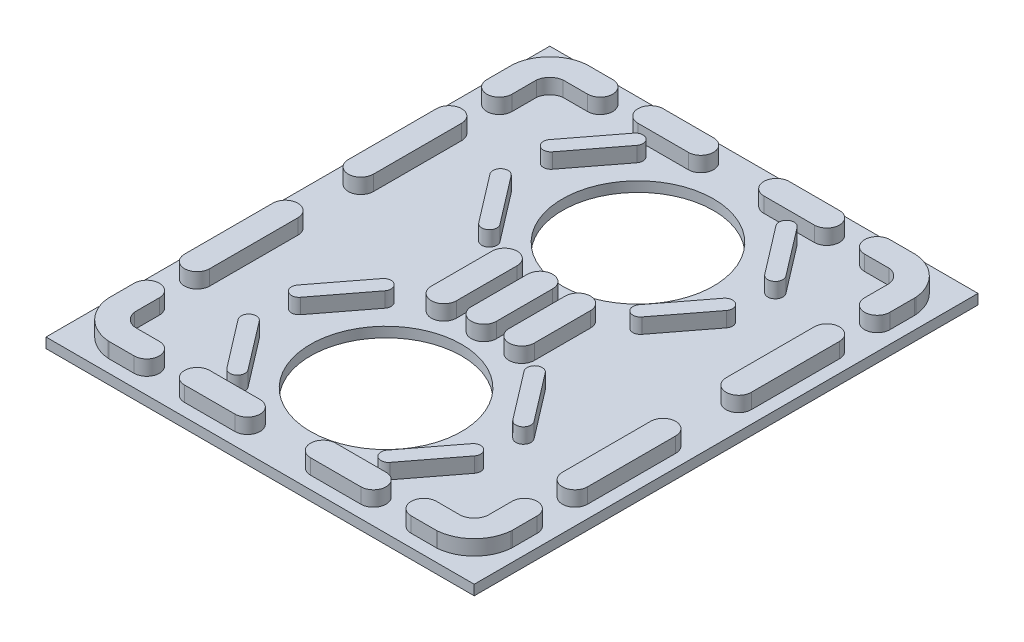
SolidWorks part; units mm, degrees
ref_plane "Front Plane" through (0, 0, 0) normal (0, 0, 1) x (1, 0, 0)
ref_plane "Top Plane" through (0, 0, 0) normal (0, 1, 0) x (1, 0, 0)
ref_plane "Right Plane" through (0, 0, 0) normal (1, 0, 0) x (0, 0, -1)
sketch "Sketch1" plane through (0, 0, 0) normal (0, 1, 0) x (1, 0, 0)
  line L1 (0, 0) -> (170, 0)
  line L2 (0, 0) -> (0, 200)
  line L3 (0, 200) -> (170, 200)
  line L4 (170, 0) -> (170, 200)
  dimension "D1" = 200
  dimension "D2" = 170
extrude "Boss-Extrude1" add sketch "Sketch1" along normal blind 4
sketch "Sketch3" plane through (0, 4, 0) normal (0, 1, 0) x (1, 0, 0)
  line L0 (0, 0) -> (20, 0)
  line L1 (0, 0) -> (170, 0) construction
  line L2 (20, 0) -> (20, 10)
  line L3 (0, 0) -> (0, 20)
  line L4 (0, 200) -> (0, 0) construction
  line L5 (0, 20) -> (10, 20)
  line L6 (10, 20) -> (10, 30) construction
  line L7 (5, 20) -> (5, 30)
  line L8 (15, 20) -> (15, 30)
  line L9 (20, 10) -> (30, 10) construction
  line L10 (20, 15) -> (30, 15)
  line L11 (20, 5) -> (30, 5)
  line L12 (0, 100) -> (170, 100) construction
  line L13 (170, 0) -> (170, 200) construction
  line L14 (85, 0) -> (85, 200) construction
  line L15 (170, 200) -> (0, 200) construction
  line L16 (10, 50) -> (10, 85) construction
  line L17 (5, 50) -> (5, 85)
  line L18 (15, 50) -> (15, 85)
  line L19 (50, 10) -> (70, 10) construction
  line L20 (50, 15) -> (70, 15)
  line L21 (50, 5) -> (70, 5)
  line L22 (160, 50) -> (160, 85) construction
  line L23 (165, 50) -> (165, 85)
  line L24 (155, 50) -> (155, 85)
  line L25 (160, 20) -> (160, 30) construction
  line L26 (165, 20) -> (165, 30)
  line L27 (155, 20) -> (155, 30)
  line L28 (150, 10) -> (140, 10) construction
  line L29 (150, 15) -> (140, 15)
  line L30 (150, 5) -> (140, 5)
  line L31 (120, 10) -> (100, 10) construction
  line L32 (120, 15) -> (100, 15)
  line L33 (120, 5) -> (100, 5)
  line L34 (160, 150) -> (160, 115) construction
  line L35 (165, 150) -> (165, 115)
  line L36 (155, 150) -> (155, 115)
  line L37 (160, 180) -> (160, 170) construction
  line L38 (165, 180) -> (165, 170)
  line L39 (155, 180) -> (155, 170)
  line L40 (150, 190) -> (140, 190) construction
  line L41 (150, 185) -> (140, 185)
  line L42 (150, 195) -> (140, 195)
  line L43 (120, 190) -> (100, 190) construction
  line L44 (120, 185) -> (100, 185)
  line L45 (120, 195) -> (100, 195)
  line L46 (50, 190) -> (70, 190) construction
  line L47 (50, 185) -> (70, 185)
  line L48 (50, 195) -> (70, 195)
  line L49 (20, 190) -> (30, 190) construction
  line L50 (20, 185) -> (30, 185)
  line L51 (20, 195) -> (30, 195)
  line L52 (10, 180) -> (10, 170) construction
  line L53 (5, 180) -> (5, 170)
  line L54 (15, 180) -> (15, 170)
  line L55 (10, 150) -> (10, 115) construction
  line L56 (5, 150) -> (5, 115)
  line L57 (15, 150) -> (15, 115)
  line L58 (170, 100) -> (170, 50) construction
  line L59 (170, 50) -> (0, 50) construction
  line L60 (170, 100) -> (170, 150) construction
  line L61 (170, 150) -> (0, 150) construction
  line L62 (85, 111.1607) -> (85, 88.8393) construction
  line L63 (90, 111.1607) -> (90, 88.8393)
  line L64 (80, 111.1607) -> (80, 88.8393)
  line L65 (100, 111.157) -> (100, 88.843) construction
  line L68 (70, 112.0369) -> (70, 87.9631) construction
  line L69 (75, 112.0369) -> (75, 87.9631)
  line L70 (65, 112.0369) -> (65, 87.9631)
  line L71 (105, 111.157) -> (105, 88.843)
  line L72 (95, 111.157) -> (95, 88.843)
  line L73 (40.4617, 40) -> (55, 21.0063) construction
  line L74 (42.844, 41.8234) -> (57.3822, 22.8297)
  line L75 (38.0795, 38.1766) -> (52.6178, 19.1828)
  line L76 (129.5383, 40) -> (115, 21.0063) construction
  line L77 (127.156, 41.8234) -> (112.6178, 22.8297)
  line L78 (131.9205, 38.1766) -> (117.3822, 19.1828)
  line L79 (129.5383, 60) -> (115, 78.9937) construction
  line L80 (127.156, 58.1766) -> (112.6178, 77.1703)
  line L81 (131.9205, 61.8234) -> (117.3822, 80.8172)
  line L82 (40.4617, 60) -> (55, 78.9937) construction
  line L83 (42.844, 58.1766) -> (57.3822, 77.1703)
  line L84 (38.0795, 61.8234) -> (52.6178, 80.8172)
  line L85 (40.4617, 160) -> (55, 178.9937) construction
  line L86 (42.844, 158.1766) -> (57.3822, 177.1703)
  line L87 (38.0795, 161.8234) -> (52.6178, 180.8172)
  line L88 (129.5383, 160) -> (115, 178.9937) construction
  line L89 (127.156, 158.1766) -> (112.6178, 177.1703)
  line L90 (131.9205, 161.8234) -> (117.3822, 180.8172)
  line L91 (129.5383, 140) -> (115, 121.0063) construction
  line L92 (127.156, 141.8234) -> (112.6178, 122.8297)
  line L93 (131.9205, 138.1766) -> (117.3822, 119.1828)
  line L94 (40.4617, 140) -> (55, 121.0063) construction
  line L95 (42.844, 141.8234) -> (57.3822, 122.8297)
  line L96 (38.0795, 138.1766) -> (52.6178, 119.1828)
  arc A1 (20, 10) -> (9.9962, 20) centre (21.0059, 21.0101) cw construction
  arc A2 (5.0171, 19.5432) -> (19.5451, 5.0207) centre (21.0059, 21.0101) ccw
  arc A3 (14.9753, 20.4568) -> (20.4549, 14.9793) centre (21.0059, 21.0101) ccw
  arc A4 (14.9753, 20.4568) -> (5.0171, 19.5432) centre (9.9962, 20) ccw
  arc A5 (19.5451, 5.0207) -> (20.4549, 14.9793) centre (20, 10) ccw
  arc A6 (5, 20) -> (15, 20) centre (10, 20) ccw
  arc A7 (15, 30) -> (5, 30) centre (10, 30) ccw
  arc A8 (20, 15) -> (20, 5) centre (20, 10) ccw
  arc A9 (30, 5) -> (30, 15) centre (30, 10) ccw
  arc A10 (5, 50) -> (15, 50) centre (10, 50) ccw
  arc A11 (15, 85) -> (5, 85) centre (10, 85) ccw
  arc A12 (50, 15) -> (50, 5) centre (50, 10) ccw
  arc A13 (70, 5) -> (70, 15) centre (70, 10) ccw
  arc A14 (165, 50) -> (155, 50) centre (160, 50) cw
  arc A15 (155, 85) -> (165, 85) centre (160, 85) cw
  arc A16 (165, 20) -> (155, 20) centre (160, 20) cw
  arc A17 (155, 30) -> (165, 30) centre (160, 30) cw
  arc A18 (150, 10) -> (160.0038, 20) centre (148.9941, 21.0101) ccw construction
  arc A19 (164.9829, 19.5432) -> (150.4549, 5.0207) centre (148.9941, 21.0101) cw
  arc A20 (155.0247, 20.4568) -> (149.5451, 14.9793) centre (148.9941, 21.0101) cw
  arc A21 (155.0247, 20.4568) -> (164.9829, 19.5432) centre (160.0038, 20) cw
  arc A22 (150.4549, 5.0207) -> (149.5451, 14.9793) centre (150, 10) cw
  arc A23 (150, 15) -> (150, 5) centre (150, 10) cw
  arc A24 (140, 5) -> (140, 15) centre (140, 10) cw
  arc A25 (120, 15) -> (120, 5) centre (120, 10) cw
  arc A26 (100, 5) -> (100, 15) centre (100, 10) cw
  arc A27 (165, 150) -> (155, 150) centre (160, 150) ccw
  arc A28 (155, 115) -> (165, 115) centre (160, 115) ccw
  arc A29 (165, 180) -> (155, 180) centre (160, 180) ccw
  arc A30 (155, 170) -> (165, 170) centre (160, 170) ccw
  arc A31 (150, 190) -> (160.0038, 180) centre (148.9941, 178.9899) cw construction
  arc A32 (164.9829, 180.4568) -> (150.4549, 194.9793) centre (148.9941, 178.9899) ccw
  arc A33 (155.0247, 179.5432) -> (149.5451, 185.0207) centre (148.9941, 178.9899) ccw
  arc A34 (155.0247, 179.5432) -> (164.9829, 180.4568) centre (160.0038, 180) ccw
  arc A35 (150.4549, 194.9793) -> (149.5451, 185.0207) centre (150, 190) ccw
  arc A36 (150, 185) -> (150, 195) centre (150, 190) ccw
  arc A37 (140, 195) -> (140, 185) centre (140, 190) ccw
  arc A38 (120, 185) -> (120, 195) centre (120, 190) ccw
  arc A39 (100, 195) -> (100, 185) centre (100, 190) ccw
  arc A40 (50, 185) -> (50, 195) centre (50, 190) cw
  arc A41 (70, 195) -> (70, 185) centre (70, 190) cw
  arc A42 (20, 185) -> (20, 195) centre (20, 190) cw
  arc A43 (30, 195) -> (30, 185) centre (30, 190) cw
  arc A44 (20, 190) -> (9.9962, 180) centre (21.0059, 178.9899) ccw construction
  arc A45 (5.0171, 180.4568) -> (19.5451, 194.9793) centre (21.0059, 178.9899) cw
  arc A46 (14.9753, 179.5432) -> (20.4549, 185.0207) centre (21.0059, 178.9899) cw
  arc A47 (14.9753, 179.5432) -> (5.0171, 180.4568) centre (9.9962, 180) cw
  arc A48 (19.5451, 194.9793) -> (20.4549, 185.0207) centre (20, 190) cw
  arc A49 (5, 180) -> (15, 180) centre (10, 180) cw
  arc A50 (15, 170) -> (5, 170) centre (10, 170) cw
  arc A51 (5, 150) -> (15, 150) centre (10, 150) cw
  arc A52 (15, 115) -> (5, 115) centre (10, 115) cw
  circle A53 centre (85, 50) radius 30
  circle A54 centre (85, 150) radius 30
  arc A55 (90, 111.1607) -> (80, 111.1607) centre (85, 111.1607) ccw
  arc A56 (80, 88.8393) -> (90, 88.8393) centre (85, 88.8393) ccw
  arc A59 (75, 112.0369) -> (65, 112.0369) centre (70, 112.0369) ccw
  arc A60 (65, 87.9631) -> (75, 87.9631) centre (70, 87.9631) ccw
  arc A61 (105, 111.157) -> (95, 111.157) centre (100, 111.157) ccw
  arc A62 (95, 88.843) -> (105, 88.843) centre (100, 88.843) ccw
  arc A63 (42.844, 41.8234) -> (38.0795, 38.1766) centre (40.4617, 40) ccw
  arc A64 (52.6178, 19.1828) -> (57.3822, 22.8297) centre (55, 21.0063) ccw
  arc A65 (127.156, 41.8234) -> (131.9205, 38.1766) centre (129.5383, 40) cw
  arc A66 (117.3822, 19.1828) -> (112.6178, 22.8297) centre (115, 21.0063) cw
  arc A67 (127.156, 58.1766) -> (131.9205, 61.8234) centre (129.5383, 60) ccw
  arc A68 (117.3822, 80.8172) -> (112.6178, 77.1703) centre (115, 78.9937) ccw
  arc A69 (42.844, 58.1766) -> (38.0795, 61.8234) centre (40.4617, 60) cw
  arc A70 (52.6178, 80.8172) -> (57.3822, 77.1703) centre (55, 78.9937) cw
  arc A71 (42.844, 158.1766) -> (38.0795, 161.8234) centre (40.4617, 160) cw
  arc A72 (52.6178, 180.8172) -> (57.3822, 177.1703) centre (55, 178.9937) cw
  arc A73 (127.156, 158.1766) -> (131.9205, 161.8234) centre (129.5383, 160) ccw
  arc A74 (117.3822, 180.8172) -> (112.6178, 177.1703) centre (115, 178.9937) ccw
  arc A75 (127.156, 141.8234) -> (131.9205, 138.1766) centre (129.5383, 140) cw
  arc A76 (117.3822, 119.1828) -> (112.6178, 122.8297) centre (115, 121.0063) cw
  arc A77 (42.844, 141.8234) -> (38.0795, 138.1766) centre (40.4617, 140) ccw
  arc A78 (52.6178, 119.1828) -> (57.3822, 122.8297) centre (55, 121.0063) ccw
  point P12 (13.1897, 13.1909)
  point P17 (10, 25)
  point P25 (25, 10)
  point P40 (10, 67.5)
  point P47 (60, 10)
  point P54 (160, 67.5)
  point P61 (160, 25)
  point P69 (156.8103, 13.1909)
  point P76 (145, 10)
  point P83 (110, 10)
  point P90 (160, 132.5)
  point P97 (160, 175)
  point P105 (156.8103, 186.8091)
  point P112 (145, 190)
  point P119 (110, 190)
  point P126 (60, 190)
  point P133 (25, 190)
  point P141 (13.1897, 186.8091)
  point P148 (10, 175)
  point P155 (10, 132.5)
  point P170 (85, 100)
  point P177 (100, 100)
  point P182 (70, 100)
  point P191 (47.7309, 30.5031)
  point P198 (122.2691, 30.5031)
  point P205 (122.2691, 69.4969)
  point P212 (47.7309, 69.4969)
  point P219 (47.7309, 169.4969)
  point P226 (122.2691, 169.4969)
  point P233 (122.2691, 130.5031)
  point P240 (47.7309, 130.5031)
  dimension "D4" = 5
  dimension "D8" = 5
  dimension "D11" = 5
  dimension "D16" = 60
  dimension "D19" = 3
  dimension "D22" = 5
  dimension "D24" = 16.0559
  dimension "D29" = 5
  dimension "D30" = 5
  dimension "D31" = 5
  dimension "D1" = 20
  dimension "D2" = 20
  dimension "D3" = 10
  dimension "D5" = 5
  dimension "D6" = 10
  dimension "D7" = 10
  dimension "D9" = 35
  dimension "D10" = 20
  dimension "D12" = 20
  dimension "D13" = 20
  dimension "D14" = 15
  dimension "D15" = 15
  dimension "D17" = 30
  dimension "D18" = 10
  dimension "D20" = 23.9191
  dimension "D21" = 21.0063
  dimension "D23" = 10
  dimension "D25" = 21.0101
  dimension "D26" = 0
  dimension "D27" = 0
  dimension "D28" = 0
  dimension "D32" = 15
  dimension "D33" = 15
extrude "Boss-Extrude2" add sketch "Sketch3" along normal blind 6
sketch "Sketch4" plane through (0, 0, 0) normal (0, 1, 0) x (1, 0, 0)
  line L0 (0, 0) -> (20, 0)
  line L2 (20, 0) -> (20, 10)
  line L3 (0, 0) -> (0, 20)
  line L5 (0, 20) -> (10, 20)
  line L6 (10, 20) -> (10, 30) construction
  line L7 (5, 20) -> (5, 30)
  line L8 (15, 20) -> (15, 30)
  line L9 (20, 10) -> (30, 10) construction
  line L10 (20, 15) -> (30, 15)
  line L11 (20, 5) -> (30, 5)
  line L12 (0, 100) -> (170, 100) construction
  line L14 (85, 0) -> (85, 200) construction
  line L16 (10, 50) -> (10, 85) construction
  line L17 (5, 50) -> (5, 85)
  line L18 (15, 50) -> (15, 85)
  line L19 (50, 10) -> (70, 10) construction
  line L20 (50, 15) -> (70, 15)
  line L21 (50, 5) -> (70, 5)
  line L22 (160, 50) -> (160, 85) construction
  line L23 (165, 50) -> (165, 85)
  line L24 (155, 50) -> (155, 85)
  line L25 (160, 20) -> (160, 30) construction
  line L26 (165, 20) -> (165, 30)
  line L27 (155, 20) -> (155, 30)
  line L28 (150, 10) -> (140, 10) construction
  line L29 (150, 15) -> (140, 15)
  line L30 (150, 5) -> (140, 5)
  line L31 (120, 10) -> (100, 10) construction
  line L32 (120, 15) -> (100, 15)
  line L33 (120, 5) -> (100, 5)
  line L34 (160, 150) -> (160, 115) construction
  line L35 (165, 150) -> (165, 115)
  line L36 (155, 150) -> (155, 115)
  line L37 (160, 180) -> (160, 170) construction
  line L38 (165, 180) -> (165, 170)
  line L39 (155, 180) -> (155, 170)
  line L40 (150, 190) -> (140, 190) construction
  line L41 (150, 185) -> (140, 185)
  line L42 (150, 195) -> (140, 195)
  line L43 (120, 190) -> (100, 190) construction
  line L44 (120, 185) -> (100, 185)
  line L45 (120, 195) -> (100, 195)
  line L46 (50, 190) -> (70, 190) construction
  line L47 (50, 185) -> (70, 185)
  line L48 (50, 195) -> (70, 195)
  line L49 (20, 190) -> (30, 190) construction
  line L50 (20, 185) -> (30, 185)
  line L51 (20, 195) -> (30, 195)
  line L52 (10, 180) -> (10, 170) construction
  line L53 (5, 180) -> (5, 170)
  line L54 (15, 180) -> (15, 170)
  line L55 (10, 150) -> (10, 115) construction
  line L56 (5, 150) -> (5, 115)
  line L57 (15, 150) -> (15, 115)
  line L58 (170, 100) -> (170, 50) construction
  line L59 (170, 50) -> (0, 50) construction
  line L60 (170, 100) -> (170, 150) construction
  line L61 (170, 150) -> (0, 150) construction
  line L62 (85, 111.1607) -> (85, 88.8393) construction
  line L63 (90, 111.1607) -> (90, 88.8393)
  line L64 (80, 111.1607) -> (80, 88.8393)
  line L65 (100, 111.157) -> (100, 88.843) construction
  line L68 (70, 112.0369) -> (70, 87.9631) construction
  line L69 (75, 112.0369) -> (75, 87.9631)
  line L70 (65, 112.0369) -> (65, 87.9631)
  line L71 (105, 111.157) -> (105, 88.843)
  line L72 (95, 111.157) -> (95, 88.843)
  line L73 (40.4617, 40) -> (55, 21.0063) construction
  line L74 (42.844, 41.8234) -> (57.3822, 22.8297)
  line L75 (38.0795, 38.1766) -> (52.6178, 19.1828)
  line L76 (129.5383, 40) -> (115, 21.0063) construction
  line L77 (127.156, 41.8234) -> (112.6178, 22.8297)
  line L78 (131.9205, 38.1766) -> (117.3822, 19.1828)
  line L79 (129.5383, 60) -> (115, 78.9937) construction
  line L80 (127.156, 58.1766) -> (112.6178, 77.1703)
  line L81 (131.9205, 61.8234) -> (117.3822, 80.8172)
  line L82 (40.4617, 60) -> (55, 78.9937) construction
  line L83 (42.844, 58.1766) -> (57.3822, 77.1703)
  line L84 (38.0795, 61.8234) -> (52.6178, 80.8172)
  line L85 (40.4617, 160) -> (55, 178.9937) construction
  line L86 (42.844, 158.1766) -> (57.3822, 177.1703)
  line L87 (38.0795, 161.8234) -> (52.6178, 180.8172)
  line L88 (129.5383, 160) -> (115, 178.9937) construction
  line L89 (127.156, 158.1766) -> (112.6178, 177.1703)
  line L90 (131.9205, 161.8234) -> (117.3822, 180.8172)
  line L91 (129.5383, 140) -> (115, 121.0063) construction
  line L92 (127.156, 141.8234) -> (112.6178, 122.8297)
  line L93 (131.9205, 138.1766) -> (117.3822, 119.1828)
  line L94 (40.4617, 140) -> (55, 121.0063) construction
  line L95 (42.844, 141.8234) -> (57.3822, 122.8297)
  line L96 (38.0795, 138.1766) -> (52.6178, 119.1828)
  arc A1 (20, 10) -> (9.9962, 20) centre (21.0059, 21.0101) cw construction
  arc A2 (5.0171, 19.5432) -> (19.5451, 5.0207) centre (21.0059, 21.0101) ccw
  arc A3 (14.9753, 20.4568) -> (20.4549, 14.9793) centre (21.0059, 21.0101) ccw
  arc A4 (14.9753, 20.4568) -> (5.0171, 19.5432) centre (9.9962, 20) ccw
  arc A5 (19.5451, 5.0207) -> (20.4549, 14.9793) centre (20, 10) ccw
  arc A6 (5, 20) -> (15, 20) centre (10, 20) ccw
  arc A7 (15, 30) -> (5, 30) centre (10, 30) ccw
  arc A8 (20, 15) -> (20, 5) centre (20, 10) ccw
  arc A9 (30, 5) -> (30, 15) centre (30, 10) ccw
  arc A10 (5, 50) -> (15, 50) centre (10, 50) ccw
  arc A11 (15, 85) -> (5, 85) centre (10, 85) ccw
  arc A12 (50, 15) -> (50, 5) centre (50, 10) ccw
  arc A13 (70, 5) -> (70, 15) centre (70, 10) ccw
  arc A14 (165, 50) -> (155, 50) centre (160, 50) cw
  arc A15 (155, 85) -> (165, 85) centre (160, 85) cw
  arc A16 (165, 20) -> (155, 20) centre (160, 20) cw
  arc A17 (155, 30) -> (165, 30) centre (160, 30) cw
  arc A18 (150, 10) -> (160.0038, 20) centre (148.9941, 21.0101) ccw construction
  arc A19 (164.9829, 19.5432) -> (150.4549, 5.0207) centre (148.9941, 21.0101) cw
  arc A20 (155.0247, 20.4568) -> (149.5451, 14.9793) centre (148.9941, 21.0101) cw
  arc A21 (155.0247, 20.4568) -> (164.9829, 19.5432) centre (160.0038, 20) cw
  arc A22 (150.4549, 5.0207) -> (149.5451, 14.9793) centre (150, 10) cw
  arc A23 (150, 15) -> (150, 5) centre (150, 10) cw
  arc A24 (140, 5) -> (140, 15) centre (140, 10) cw
  arc A25 (120, 15) -> (120, 5) centre (120, 10) cw
  arc A26 (100, 5) -> (100, 15) centre (100, 10) cw
  arc A27 (165, 150) -> (155, 150) centre (160, 150) ccw
  arc A28 (155, 115) -> (165, 115) centre (160, 115) ccw
  arc A29 (165, 180) -> (155, 180) centre (160, 180) ccw
  arc A30 (155, 170) -> (165, 170) centre (160, 170) ccw
  arc A31 (150, 190) -> (160.0038, 180) centre (148.9941, 178.9899) cw construction
  arc A32 (164.9829, 180.4568) -> (150.4549, 194.9793) centre (148.9941, 178.9899) ccw
  arc A33 (155.0247, 179.5432) -> (149.5451, 185.0207) centre (148.9941, 178.9899) ccw
  arc A34 (155.0247, 179.5432) -> (164.9829, 180.4568) centre (160.0038, 180) ccw
  arc A35 (150.4549, 194.9793) -> (149.5451, 185.0207) centre (150, 190) ccw
  arc A36 (150, 185) -> (150, 195) centre (150, 190) ccw
  arc A37 (140, 195) -> (140, 185) centre (140, 190) ccw
  arc A38 (120, 185) -> (120, 195) centre (120, 190) ccw
  arc A39 (100, 195) -> (100, 185) centre (100, 190) ccw
  arc A40 (50, 185) -> (50, 195) centre (50, 190) cw
  arc A41 (70, 195) -> (70, 185) centre (70, 190) cw
  arc A42 (20, 185) -> (20, 195) centre (20, 190) cw
  arc A43 (30, 195) -> (30, 185) centre (30, 190) cw
  arc A44 (20, 190) -> (9.9962, 180) centre (21.0059, 178.9899) ccw construction
  arc A45 (5.0171, 180.4568) -> (19.5451, 194.9793) centre (21.0059, 178.9899) cw
  arc A46 (14.9753, 179.5432) -> (20.4549, 185.0207) centre (21.0059, 178.9899) cw
  arc A47 (14.9753, 179.5432) -> (5.0171, 180.4568) centre (9.9962, 180) cw
  arc A48 (19.5451, 194.9793) -> (20.4549, 185.0207) centre (20, 190) cw
  arc A49 (5, 180) -> (15, 180) centre (10, 180) cw
  arc A50 (15, 170) -> (5, 170) centre (10, 170) cw
  arc A51 (5, 150) -> (15, 150) centre (10, 150) cw
  arc A52 (15, 115) -> (5, 115) centre (10, 115) cw
  circle A53 centre (85, 50) radius 30
  circle A54 centre (85, 150) radius 30
  arc A55 (90, 111.1607) -> (80, 111.1607) centre (85, 111.1607) ccw
  arc A56 (80, 88.8393) -> (90, 88.8393) centre (85, 88.8393) ccw
  arc A59 (75, 112.0369) -> (65, 112.0369) centre (70, 112.0369) ccw
  arc A60 (65, 87.9631) -> (75, 87.9631) centre (70, 87.9631) ccw
  arc A61 (105, 111.157) -> (95, 111.157) centre (100, 111.157) ccw
  arc A62 (95, 88.843) -> (105, 88.843) centre (100, 88.843) ccw
  arc A63 (42.844, 41.8234) -> (38.0795, 38.1766) centre (40.4617, 40) ccw
  arc A64 (52.6178, 19.1828) -> (57.3822, 22.8297) centre (55, 21.0063) ccw
  arc A65 (127.156, 41.8234) -> (131.9205, 38.1766) centre (129.5383, 40) cw
  arc A66 (117.3822, 19.1828) -> (112.6178, 22.8297) centre (115, 21.0063) cw
  arc A67 (127.156, 58.1766) -> (131.9205, 61.8234) centre (129.5383, 60) ccw
  arc A68 (117.3822, 80.8172) -> (112.6178, 77.1703) centre (115, 78.9937) ccw
  arc A69 (42.844, 58.1766) -> (38.0795, 61.8234) centre (40.4617, 60) cw
  arc A70 (52.6178, 80.8172) -> (57.3822, 77.1703) centre (55, 78.9937) cw
  arc A71 (42.844, 158.1766) -> (38.0795, 161.8234) centre (40.4617, 160) cw
  arc A72 (52.6178, 180.8172) -> (57.3822, 177.1703) centre (55, 178.9937) cw
  arc A73 (127.156, 158.1766) -> (131.9205, 161.8234) centre (129.5383, 160) ccw
  arc A74 (117.3822, 180.8172) -> (112.6178, 177.1703) centre (115, 178.9937) ccw
  arc A75 (127.156, 141.8234) -> (131.9205, 138.1766) centre (129.5383, 140) cw
  arc A76 (117.3822, 119.1828) -> (112.6178, 122.8297) centre (115, 121.0063) cw
  arc A77 (42.844, 141.8234) -> (38.0795, 138.1766) centre (40.4617, 140) ccw
  arc A78 (52.6178, 119.1828) -> (57.3822, 122.8297) centre (55, 121.0063) ccw
  point P12 (13.1897, 13.1909)
  point P17 (10, 25)
  point P25 (25, 10)
  point P40 (10, 67.5)
  point P47 (60, 10)
  point P54 (160, 67.5)
  point P61 (160, 25)
  point P69 (156.8103, 13.1909)
  point P76 (145, 10)
  point P83 (110, 10)
  point P90 (160, 132.5)
  point P97 (160, 175)
  point P105 (156.8103, 186.8091)
  point P112 (145, 190)
  point P119 (110, 190)
  point P126 (60, 190)
  point P133 (25, 190)
  point P141 (13.1897, 186.8091)
  point P148 (10, 175)
  point P155 (10, 132.5)
  point P170 (85, 100)
  point P177 (100, 100)
  point P182 (70, 100)
  point P191 (47.7309, 30.5031)
  point P198 (122.2691, 30.5031)
  point P205 (122.2691, 69.4969)
  point P212 (47.7309, 69.4969)
  point P219 (47.7309, 169.4969)
  point P226 (122.2691, 169.4969)
  point P233 (122.2691, 130.5031)
  point P240 (47.7309, 130.5031)
  dimension "D4" = 5
  dimension "D8" = 5
  dimension "D11" = 5
  dimension "D16" = 60
  dimension "D19" = 3
  dimension "D22" = 5
  dimension "D24" = 16.0559
  dimension "D29" = 5
  dimension "D30" = 5
  dimension "D31" = 5
  dimension "D1" = 20
  dimension "D2" = 20
  dimension "D3" = 10
  dimension "D5" = 5
  dimension "D6" = 10
  dimension "D7" = 10
  dimension "D9" = 35
  dimension "D10" = 20
  dimension "D12" = 20
  dimension "D13" = 20
  dimension "D14" = 15
  dimension "D15" = 15
  dimension "D17" = 30
  dimension "D18" = 10
  dimension "D20" = 23.9191
  dimension "D26" = 0
  dimension "D27" = 0
  dimension "D28" = 0
  dimension "D32" = 15
  dimension "D33" = 15
extrude "Cut-Extrude2" cut sketch "Sketch4" against normal blind 10 and the other way through all contours A53 | A54
